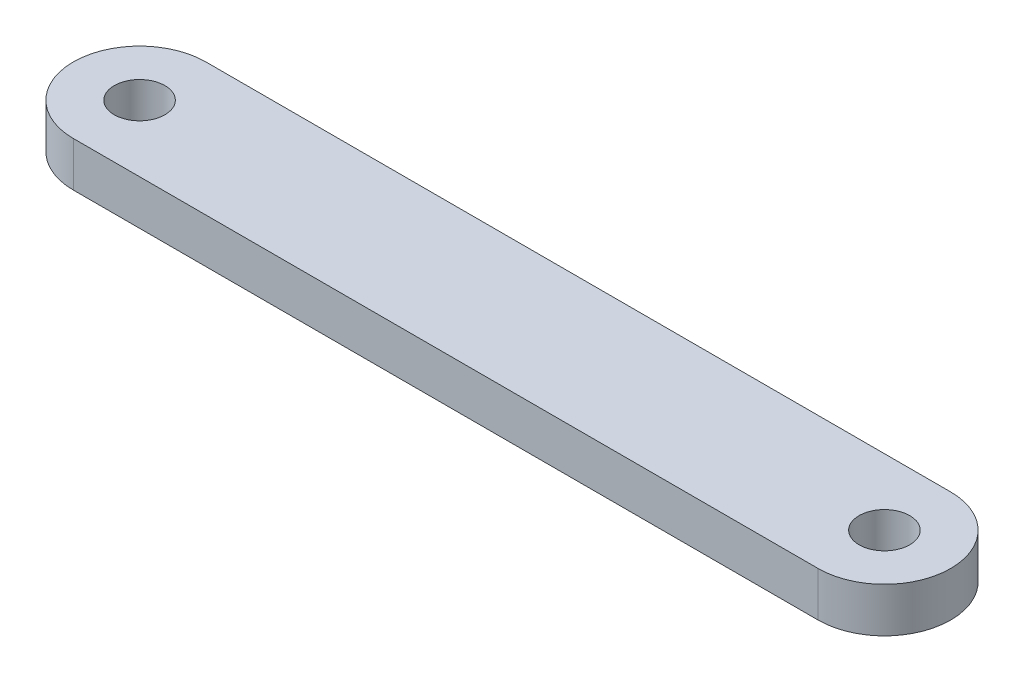
SolidWorks part; units mm, degrees
ref_plane "Front Plane" through (0, 0, 0) normal (0, 0, 1) x (1, 0, 0)
ref_plane "Top Plane" through (0, 0, 0) normal (0, 1, 0) x (1, 0, 0)
ref_plane "Right Plane" through (0, 0, 0) normal (1, 0, 0) x (0, 0, -1)
sketch "Sketch1" plane through (0, 0, 0) normal (0, 1, 0) x (1, 0, 0)
  line L0 (0, 0) -> (50, 0)
  line L2 (0, 4.45) -> (50, 4.45)
  line L4 (0, -4.45) -> (50, -4.45)
  circle A0 centre (0, 0) radius 1.45
  circle A1 centre (0, 0) radius 1.45
  circle A2 centre (50, 0) radius 1.45
  circle A3 centre (50, 0) radius 4.45
  circle A4 centre (0, 0) radius 4.45
  dimension "D1" = 3
extrude "Boss-Extrude1" add sketch "Sketch1" along normal blind 3
sketch "Sketch2" plane through (0, 3, 0) normal (0, 1, 0) x (1, 0, 0)
  circle A0 centre (0, 0) radius 1.7
  circle A1 centre (50, 0) radius 1.7
extrude "Cut-Extrude1" cut sketch "Sketch2" against normal through all
